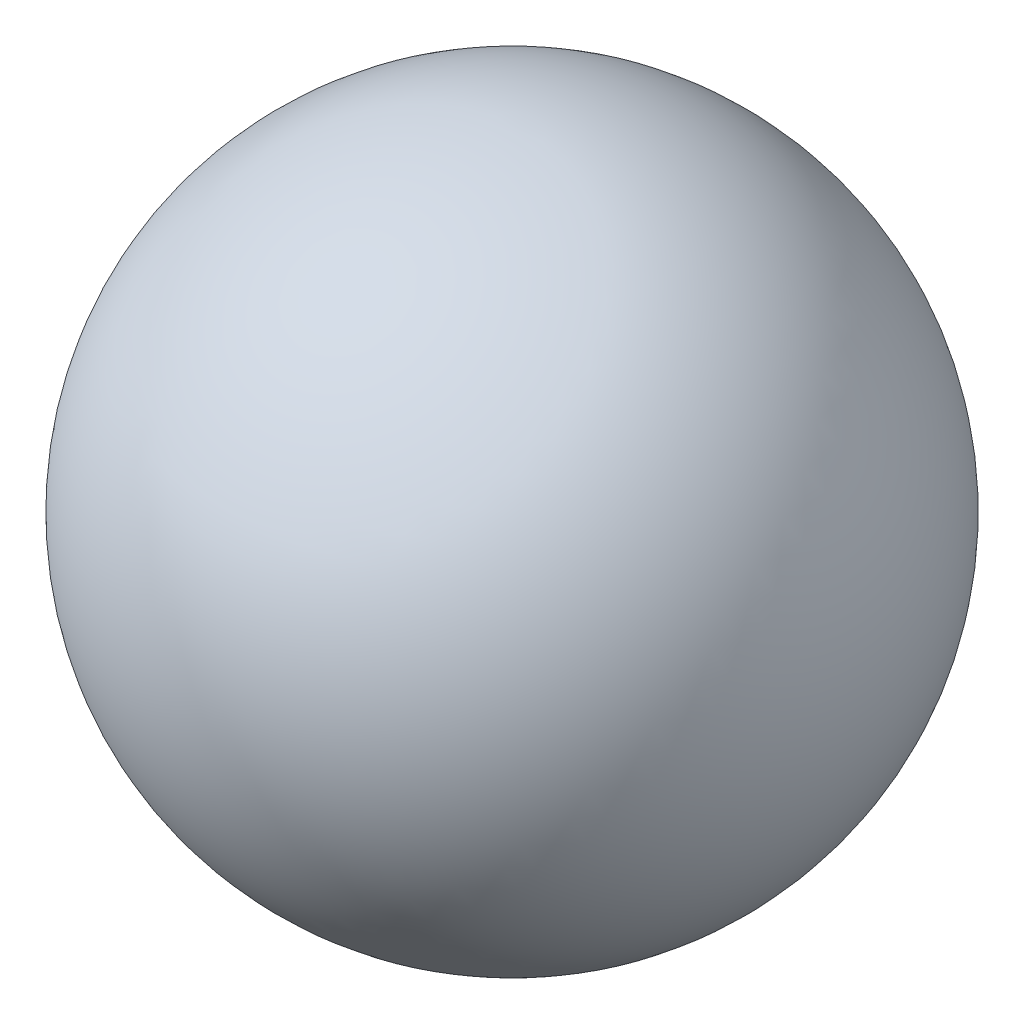
SolidWorks part; units mm, degrees
ref_plane "Front Plane" through (0, 0, 0) normal (0, 0, 1) x (1, 0, 0)
ref_plane "Top Plane" through (0, 0, 0) normal (0, 1, 0) x (1, 0, 0)
ref_plane "Right Plane" through (0, 0, 0) normal (1, 0, 0) x (0, 0, -1)
sketch "Sketch1" plane through (0, 0, 0) normal (0, 0, 1) x (1, 0, 0)
  line L0 (0, 12.5) -> (0, -12.5)
  arc A0 (0, -12.5) -> (0, 12.5) centre (0, 0) ccw
  dimension "D1" = 25
revolve "Revolve1" add sketch "Sketch1" angle 360 about L0
